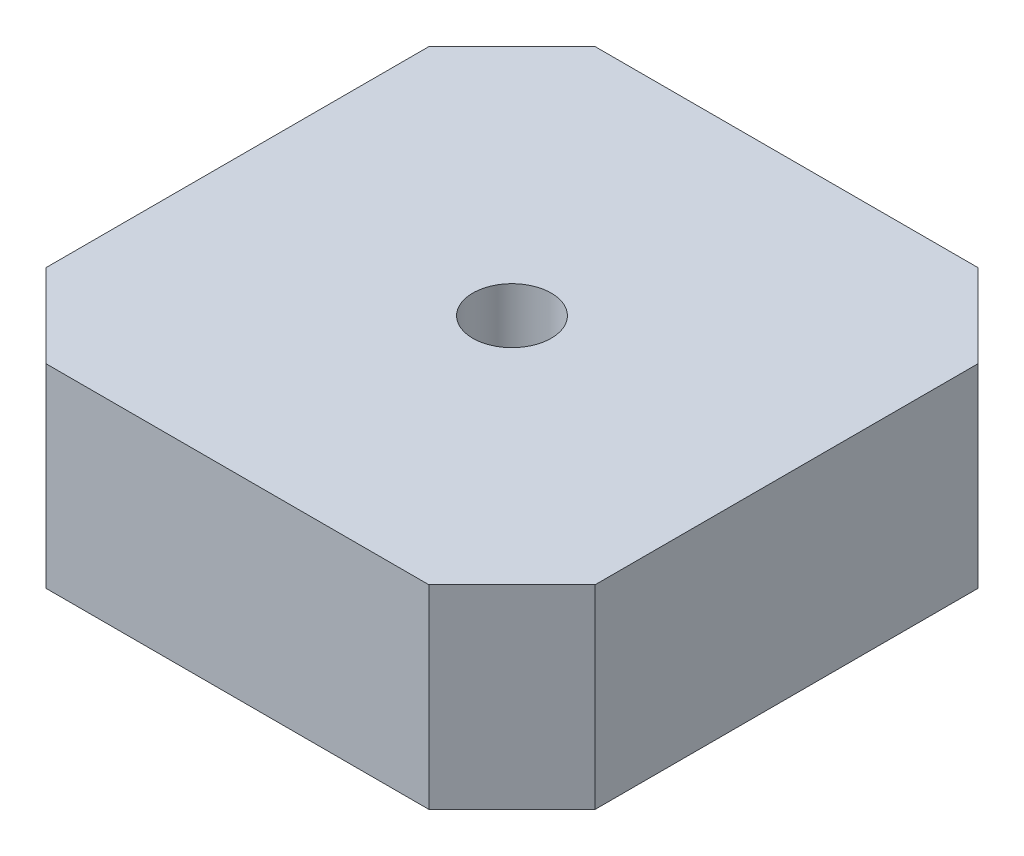
SolidWorks part; units mm, degrees
material "Hierro dúctil"
ref_plane "Alzado" through (0, 0, 0) normal (0, 0, 1) x (1, 0, 0)
ref_plane "Planta" through (0, 0, 0) normal (0, 1, 0) x (1, 0, 0)
ref_plane "Vista lateral" through (0, 0, 0) normal (1, 0, 0) x (0, 0, -1)
sketch "Croquis1" plane through (0, 0, 0) normal (0, 1, 0) x (1, 0, 0)
  line L1 (0, 0) -> (35, 0)
  line L2 (0, 0) -> (0, 35)
  line L3 (0, 35) -> (35, 35)
  line L4 (35, 0) -> (35, 35)
  dimension "D1" = 35
  dimension "D2" = 35
extrude "Saliente-Extruir1" add sketch "Croquis1" along normal blind 12.4
sketch "Croquis2" plane through (0, 12.4, 0) normal (0, 1, 0) x (1, 0, 0)
  line L0 (5.3015, 35) -> (0, 29.6985)
  line L1 (35, 35) -> (0, 35) construction
  line L2 (0, 35) -> (0, 0) construction
  line L3 (0, 29.6985) -> (0, 5.3015)
  line L4 (0, 5.3015) -> (5.3015, 0)
  line L5 (0, 0) -> (35, 0) construction
  line L6 (5.3015, 0) -> (29.6985, 0)
  line L7 (29.6985, 0) -> (35, 5.3015)
  line L8 (35, 0) -> (35, 35) construction
  line L9 (35, 5.3015) -> (35, 29.6985)
  line L10 (35, 29.6985) -> (29.6985, 35)
  line L11 (29.6985, 35) -> (5.3015, 35)
  dimension "D1" = 42
  dimension "D2" = 42
  dimension "D3" = 45
extrude "Cortar-Extruir2" cut sketch "Croquis2" against normal blind 18 flip side to cut
sketch "Croquis3" plane through (0, 12.4, 0) normal (0, 1, 0) x (1, 0, 0)
  line L0 (17.5, 35) -> (17.5, 0) construction
  line L1 (29.6985, 35) -> (5.3015, 35) construction
  line L2 (5.3015, 0) -> (29.6985, 0) construction
  circle A0 centre (17.5, 17.5) radius 2.5
  dimension "D1" = 5
extrude "Cortar-Extruir3" cut sketch "Croquis3" against normal through all
